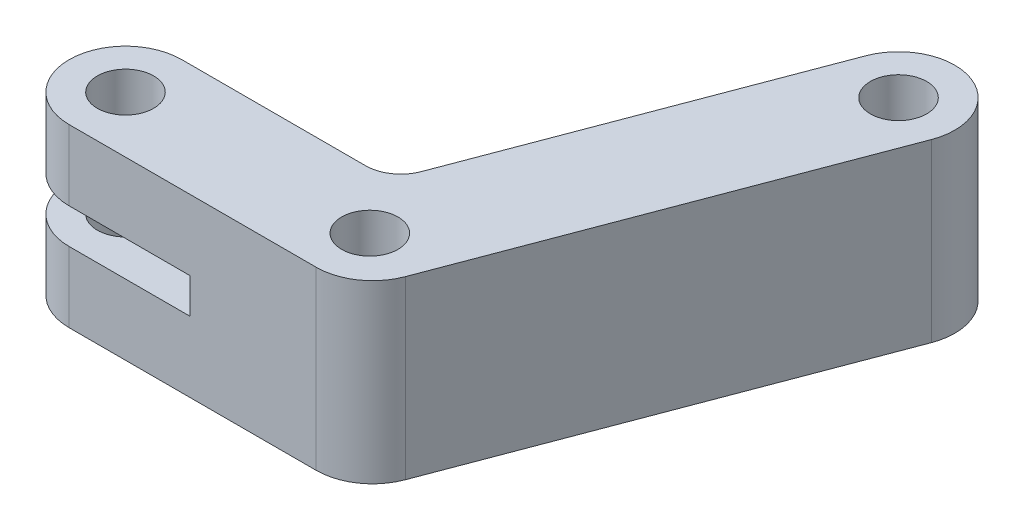
SolidWorks part; units mm, degrees
ref_plane "Front Plane" through (0, 0, 0) normal (0, 0, 1) x (1, 0, 0)
ref_plane "Top Plane" through (0, 0, 0) normal (0, 1, 0) x (1, 0, 0)
ref_plane "Right Plane" through (0, 0, 0) normal (1, 0, 0) x (0, 0, -1)
sketch "Sketch1" plane through (0, 0, 0) normal (0, 1, 0) x (1, 0, 0)
  line L0 (0, 0) -> (35.1066, 0)
  line L1 (42.5898, 5.1713) -> (63.0932, 59.4113)
  line L2 (63.61, 82.4129) -> (63.61, -30.9074) construction
  line L3 (0, 16) -> (26.123, 16)
  line L4 (30.8, 19.232) -> (48.1268, 65.0687)
  line L6 (-33.1935, 70.24) -> (97.4092, 70.24) construction
  arc A1 (0, 16) -> (0, 0) centre (0, 8) ccw
  arc A2 (48.1268, 65.0687) -> (63.0932, 59.4113) centre (55.61, 62.24) cw
  circle A3 centre (0, 8) radius 4
  circle A4 centre (55.61, 62.24) radius 4
  circle A5 centre (34.72, 8) radius 4
  arc A6 (35.1066, 0) -> (42.5898, 5.1713) centre (35.1066, 8) ccw
  arc A7 (30.8, 19.232) -> (26.123, 16) centre (26.123, 21) cw
  point P11 (-8, 8)
  dimension "D3" = 8
  dimension "D6" = 71.61
  dimension "D8" = 8
  dimension "D9" = 5
  dimension "D1" = 16
  dimension "D2" = 16
  dimension "D4" = 34.72
  dimension "D5" = 54.24
  dimension "D7" = 70.24
extrude "Boss-Extrude1" add sketch "Sketch1" along normal blind 25
sketch "Sketch2" plane through (0, 0, 0) normal (0, 0, 1) x (1, 0, 0)
  line L0 (-8, 25) -> (-8, 0) construction
  line L1 (-8, 15) -> (17.15, 15)
  line L2 (-8, 15) -> (-8, 10)
  line L3 (-8, 10) -> (17.15, 10)
  line L4 (17.15, 15) -> (17.15, 10)
  dimension "D1" = 25.15
  dimension "D2" = 5
  dimension "D3" = 10
extrude "Cut-Extrude1" cut sketch "Sketch2" against normal blind 20
